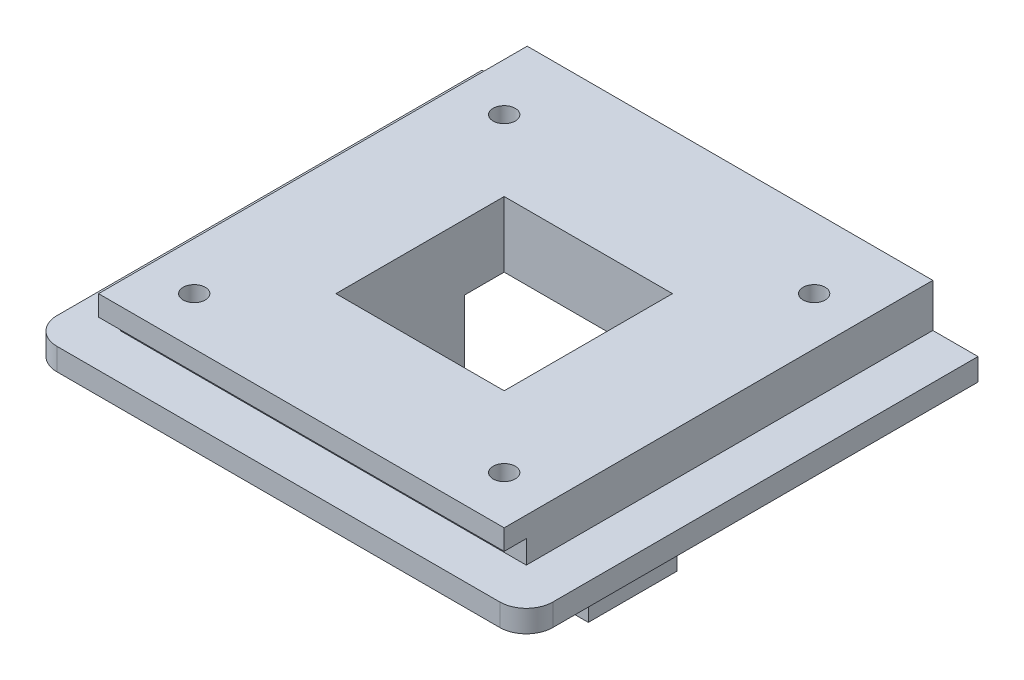
SolidWorks part; units mm, degrees
ref_plane "Front Plane" through (0, 0, 0) normal (0, 0, 1) x (1, 0, 0)
ref_plane "Top Plane" through (0, 0, 0) normal (0, 1, 0) x (1, 0, 0)
ref_plane "Right Plane" through (0, 0, 0) normal (1, 0, 0) x (0, 0, -1)
sketch "Sketch1" plane through (0, 0, 0) normal (0, 1, 0) x (1, 0, 0)
  line L1 (0, 0) -> (46, 0)
  line L2 (0, 0) -> (0, 46)
  line L3 (0, 46) -> (46, 46)
  line L4 (46, 0) -> (46, 46)
  dimension "D1" = 46
  dimension "D2" = 46
extrude "Boss-Extrude1" add sketch "Sketch1" along normal blind 2.5
sketch "Sketch2" plane through (0, 2.5, 0) normal (0, 1, 0) x (1, 0, 0)
  line L0 (46, 0) -> (46, 46) construction
  line L1 (0, 46) -> (46, 46)
  line L2 (0, 46) -> (0, -2.5)
  line L3 (0, -2.5) -> (46, -2.5)
  line L4 (46, 46) -> (46, -2.5)
  line L5 (0, 0) -> (46, 0) construction
  dimension "D1" = 2.5
extrude "Boss-Extrude2" add sketch "Sketch2" along normal blind 2.5
sketch "Sketch3" plane through (0, 0, 0) normal (0, -1, 0) x (1, 0, 0)
  line L0 (46, -46) -> (0, -46) construction
  line L1 (-5, 5) -> (51, 5)
  line L2 (-5, 5) -> (-5, -46)
  line L3 (-5, -46) -> (51, -46)
  line L4 (51, 5) -> (51, -46)
  line L5 (-5, 5) -> (51, -46) construction
  line L6 (-5, -46) -> (51, 5) construction
  line L7 (23, -46) -> (23, 0) construction
  line L8 (0, 0) -> (46, 0) construction
  point P0 (23, -20.5)
  dimension "D1" = 56
  dimension "D2" = 51
extrude "Boss-Extrude3" add sketch "Sketch3" along normal blind 2.5
sketch "Sketch7" plane through (0, -2.5, 0) normal (0, -1, 0) x (1, 0, 0)
  line L0 (23, 5) -> (23, -46) construction
  line L1 (51, 5) -> (-5, 5) construction
  line L2 (-5, -46) -> (51, -46) construction
  line L3 (8.5, -15.5) -> (13.5, -15.5)
  line L4 (8.5, -15.5) -> (8.5, -25.5)
  line L5 (8.5, -25.5) -> (13.5, -25.5)
  line L6 (13.5, -15.5) -> (13.5, -25.5)
  line L11 (32.5, -15.5) -> (32.5, -25.5)
  line L12 (37.5, -25.5) -> (32.5, -25.5)
  line L13 (37.5, -15.5) -> (37.5, -25.5)
  line L14 (37.5, -15.5) -> (32.5, -15.5)
  point P8 (13.5, -20.5)
  point P9 (23, -20.5)
  dimension "D1" = 5
  dimension "D2" = 10
  dimension "D3" = 9.5
extrude "Boss-Extrude6" add sketch "Sketch7" along normal blind 15
hole_wizard "CBORE for M2.5 SHCS1" positions "Sketch8" profile "Sketch10" counterbore size "M2.5" standard "ANSI Metric"
sketch "Sketch8" plane through (8.5, 0, 0) normal (-1, 0, 0) x (0, 0, 1)
  line L0 (-25.5, -10.5) -> (-15.5, -10.5) construction
  line L1 (-25.5, -17.5) -> (-25.5, -2.5) construction
  line L2 (-15.5, -17.5) -> (-15.5, -2.5) construction
  line L4 (-15.5, -2.5) -> (-25.5, -2.5) construction
  point P0 (-20.5, -10.5)
  dimension "D1" = 8
sketch "Sketch10" plane through (8.5, -10.5, -20.5) normal (0, 1, 0) x (0, 0, 1)
  line L0 (0, 0) -> (0, 5.9313)
  line L1 (0, 5.9313) -> (1.55, 5)
  line L2 (1.55, 5) -> (1.55, 3.5)
  line L3 (1.55, 3.5) -> (2.75, 3.5)
  line L4 (2.75, 3.5) -> (2.75, 0)
  line L5 (2.75, 0) -> (0, 0)
  line L10 (0, 5.9313) -> (-1.55, 5) construction
  line L11 (0, -6.35) -> (0, 107.95) construction
  dimension "Hole Dia." = 3.1
  dimension "Hole Depth" = 5
  dimension "C'Bore Dia." = 5.5
  dimension "C'Bore Depth" = 3.5
  dimension "Drill Angle" = 118
sketch "Sketch11" plane through (0, -2.5, 0) normal (0, -1, 0) x (1, 0, 0)
  line L1 (13.5, -11) -> (32.5, -11)
  line L2 (13.5, -11) -> (13.5, -30)
  line L3 (13.5, -30) -> (32.5, -30)
  line L4 (32.5, -11) -> (32.5, -30)
  line L6 (13.5, -25.5) -> (13.5, -15.5) construction
  line L7 (32.5, -15.5) -> (32.5, -25.5) construction
  line L8 (32.5, -15.5) -> (32.5, -25.5) construction
  point P10 (32.5, -20.5)
  point P11 (32.5, -20.5)
  dimension "D1" = 19
extrude "Cut-Extrude2" cut sketch "Sketch11" against normal through all
hole_wizard "M3x0.5 Tapped Hole1" positions "Sketch12" profile "Sketch13" tap size "M3x0.5" standard "ANSI Metric" end condition through all
sketch "Sketch12" plane through (0, 5, 0) normal (0, 1, 0) x (1, 0, 0)
  line L0 (5.5, 38) -> (0, 38) construction
  line L1 (0, 46) -> (0, -2.5) construction
  line L3 (40.5, 38) -> (46, 38) construction
  line L4 (46, -2.5) -> (46, 46) construction
  line L11 (46, 46) -> (0, 46) construction
  point P0 (5.5, 38)
  point P2 (40.5, 38)
  point P4 (40.5, 3)
  point P6 (5.5, 3)
  dimension "D1" = 35
  dimension "D2" = 35
  dimension "D3" = 8
cosmetic thread "Hole Thread1" parameters "D2"=3
cosmetic thread "Hole Thread2" parameters "D2"=3
cosmetic thread "Hole Thread3" parameters "D2"=3
cosmetic thread "Hole Thread4" parameters "D2"=3
sketch "Sketch13" plane through (5.5, 5, -38) normal (1, 0, 0) x (0, 0, 1)
  line L0 (0, 0) -> (0, 22.5)
  line L1 (0, 22.5) -> (1.25, 22.5)
  line L2 (1.25, 22.5) -> (1.25, 0)
  line L5 (1.25, 0) -> (0, 0)
  line L11 (0, -6.35) -> (0, 107.95) construction
  dimension "Thru Tap Drill Dia." = 2.5
  dimension "Thru Tap Drill Depth" = 22.5
fillet "Fillet1" radius 3 2 edges at (51, -1.25, 5) (-5, -1.25, 5)
other "Move Face1" face at (5.5, 5, -36.75) face at (23, 2.5, 1.25) face at (23, 3.75, 2.5) face at (23, 1.25, 0) parameters "D1"=0.1
other "Move Face2" face at (0, 2.5, -14.5667) face at (46, 2.5, -14.5667) parameters "D1"=0.1
hole_wizard "M2.5x0.45 Tapped Hole1" positions "Sketch14" profile "Sketch15" tap size "M2.5x0.45" standard "ANSI Metric"
sketch "Sketch14" plane through (0, 0, -46) normal (0, 0, -1) x (-1, 0, 0)
  line L0 (-45.9, 4.9) -> (-0.1, 4.9) construction
  line L1 (5, -2.5) -> (5, 0) construction
  line L2 (-51, -2.5) -> (-51, 0) construction
  point P0 (-36, 1.9)
  point P2 (-10, 1.9)
  dimension "D1" = 3
  dimension "D2" = 15
  dimension "D3" = 15
sketch "Sketch15" plane through (36, 1.9, -46) normal (1, 0, 0) x (0, 1, 0)
  line L0 (0, 0) -> (0, 5.6159)
  line L1 (0, 5.6159) -> (1.025, 5)
  line L2 (1.025, 5) -> (1.025, 0)
  line L5 (1.025, 0) -> (0, 0)
  line L10 (0, 5.6159) -> (-1.025, 5) construction
  line L11 (0, -6.35) -> (0, 107.95) construction
  dimension "Tap Drill Dia." = 2.05
  dimension "Tap Drill Depth" = 5
  dimension "Drill Angle" = 118
cosmetic thread "Hole Thread5" parameters "D1"=5, "D2"=2.5
cosmetic thread "Hole Thread6" parameters "D1"=5, "D2"=2.5
hole_wizard "CBORE for M2.5 SHCS2" positions "Sketch16" profile "Sketch17" counterbore size "M2.5" standard "ANSI Metric"
sketch "Sketch16" plane through (37.5, 0, 0) normal (1, 0, 0) x (0, 0, -1)
  line L0 (20.5, -17.5) -> (20.5, -2.5) construction
  line L1 (25.5, -17.5) -> (15.5, -17.5) construction
  line L2 (25.5, -2.5) -> (15.5, -2.5) construction
  point P0 (20.5, -10.5)
  dimension "D1" = 8
sketch "Sketch17" plane through (37.5, -10.5, -20.5) normal (0, 1, 0) x (0, 0, -1)
  line L0 (0, 0) -> (0, 5.9313)
  line L1 (0, 5.9313) -> (1.55, 5)
  line L2 (1.55, 5) -> (1.55, 3.5)
  line L3 (1.55, 3.5) -> (2.75, 3.5)
  line L4 (2.75, 3.5) -> (2.75, 0)
  line L5 (2.75, 0) -> (0, 0)
  line L10 (0, 5.9313) -> (-1.55, 5) construction
  line L11 (0, -6.35) -> (0, 107.95) construction
  dimension "Hole Dia." = 3.1
  dimension "Hole Depth" = 5
  dimension "C'Bore Dia." = 5.5
  dimension "C'Bore Depth" = 3.5
  dimension "Drill Angle" = 118
